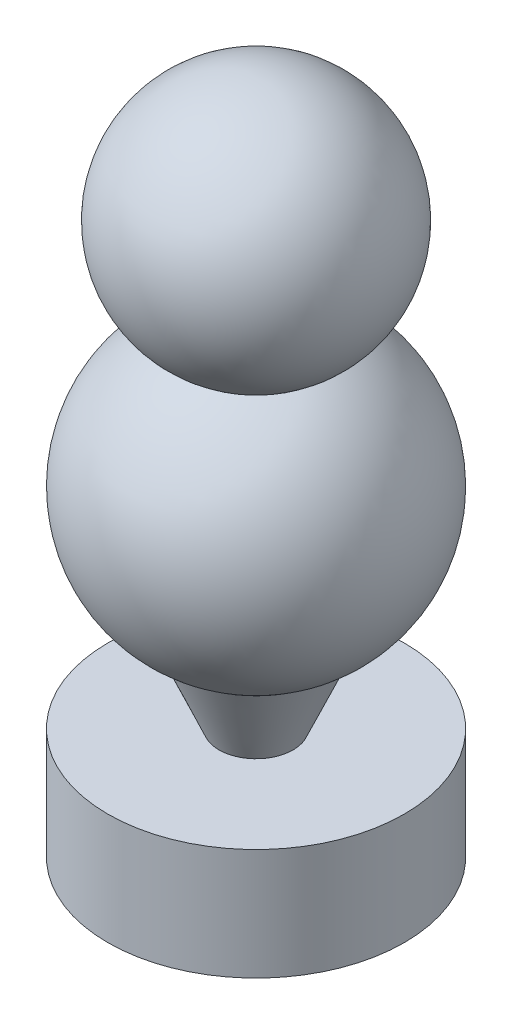
SolidWorks part; units mm, degrees
ref_plane "Front Plane" through (0, 0, 0) normal (0, 0, 1) x (1, 0, 0)
ref_plane "Top Plane" through (0, 0, 0) normal (0, 1, 0) x (1, 0, 0)
ref_plane "Right Plane" through (0, 0, 0) normal (1, 0, 0) x (0, 0, -1)
sketch "Sketch1" plane through (0, 0, 0) normal (0, 0, 1) x (1, 0, 0)
  line L0 (3, -35.6165) -> (12, -35.6165)
  line L3 (0, -44.6302) -> (12, -44.6302)
  line L4 (12, -35.6165) -> (12, -44.6302)
  line L5 (0, -44.6302) -> (12, -44.6302)
  line L8 (12, -44.6302) -> (12, -35.6165)
  line L9 (0, 10) -> (0, -44.6302) construction
  line L12 (3, -35.6165) -> (5.8167, -29.1262)
  arc A0 (5.8167, -8.1342) -> (0, 10) centre (0, 0) ccw
  arc A2 (5.8167, -29.1262) -> (5.8167, -8.1342) centre (0, -18.6302) ccw
  dimension "D1" = 20
  dimension "D2" = 12
  dimension "D3" = 9
  dimension "D4" = 26
  dimension "D5" = 12
revolve "Revolve7" add sketch "Sketch1" angle 360 about L9
